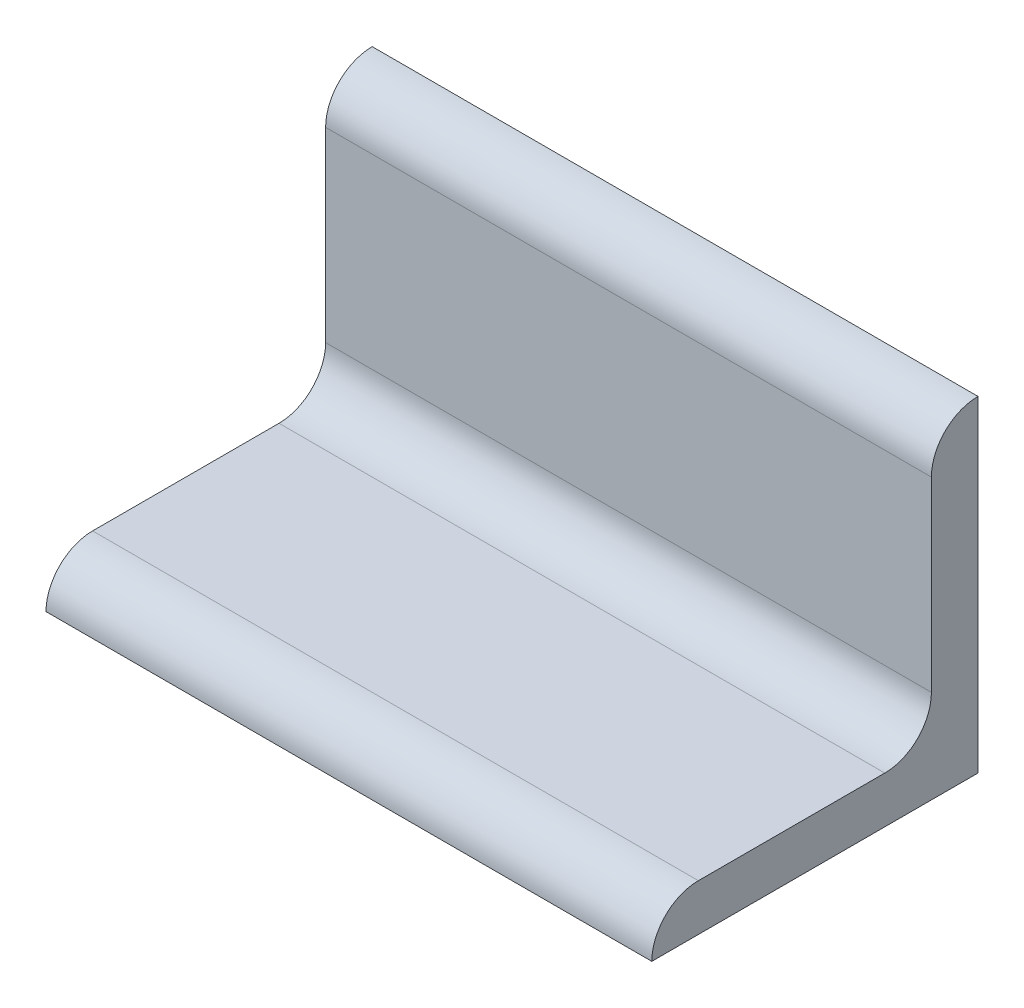
SolidWorks part; units mm, degrees
ref_plane "Front" through (0, 0, 0) normal (0, 0, 1) x (1, 0, 0)
ref_plane "Top" through (0, 0, 0) normal (0, 1, 0) x (1, 0, 0)
ref_plane "Right" through (0, 0, 0) normal (1, 0, 0) x (0, 0, -1)
sketch "Sketch1" plane through (0, 0, 0) normal (0, 0, 1) x (1, 0, 0)
  line L0 (-32.2292, 0) -> (32.7708, 0)
  dimension "D1" = 65
other "Angle iron 35 X 35 X 5(1)"
ref_plane "Plane1" through (-32.2292, 0, 0) normal (1, 0, 0) x (0, 1, 0)
sketch "Sketch11" plane through (-32.2292, 0, 0) normal (1, 0, 0) x (0, 1, 0)
  line L0 (0, 0) -> (0, 35)
  line L1 (0, 17.5) -> (5, 17.5) construction
  line L2 (5, 30) -> (5, 10)
  line L3 (10, 5) -> (30, 5)
  line L4 (17.5, 5) -> (17.5, 0) construction
  line L5 (35, 0) -> (0, 0)
  arc A0 (35, 0) -> (30, 5) centre (30, 0) ccw
  arc A1 (0, 35) -> (5, 30) centre (0, 30) cw
  arc A2 (10, 5) -> (5, 10) centre (10, 10) cw
  point P10 (17.5, 0)
  point P14 (0, 17.5)
  point P15 (5, 17.5)
  point P16 (17.5, 5)
  point P17 (5, 35)
  point P18 (35, 5)
  point P21 (0, 0)
  dimension "D2" = 5
  dimension "D3" = 35
  dimension "Radius_1" = 5
  dimension "D1" = 5
